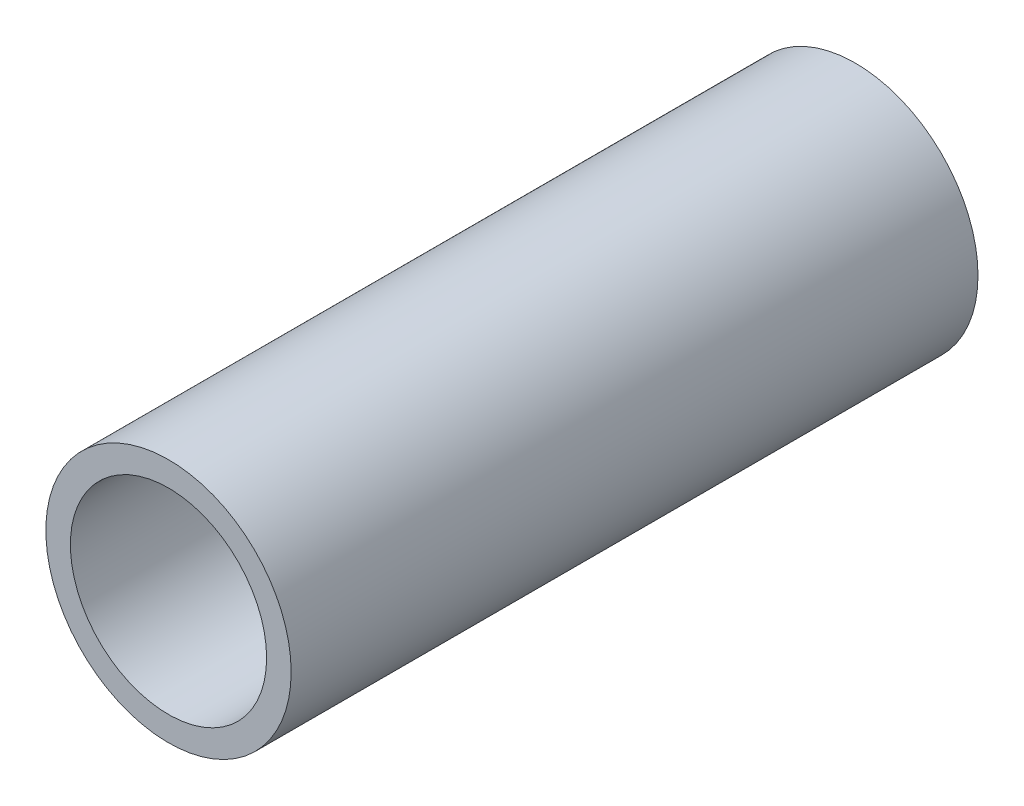
SolidWorks part; units mm, degrees
material "Nylon 101"
ref_plane "Front Plane" through (0, 0, 0) normal (0, 0, 1) x (1, 0, 0)
ref_plane "Top Plane" through (0, 0, 0) normal (0, 1, 0) x (1, 0, 0)
ref_plane "Right Plane" through (0, 0, 0) normal (1, 0, 0) x (0, 0, -1)
sketch "Sketch1" plane through (0, 0, 0) normal (0, 0, 1) x (1, 0, 0)
  circle A0 centre (0, 0) radius 6.35
  circle A1 centre (0, 0) radius 7.9375
  dimension "D1" = 12.7
  dimension "D2" = 15.875
extrude "Boss-Extrude1" add sketch "Sketch1" along normal mid plane 44.45
